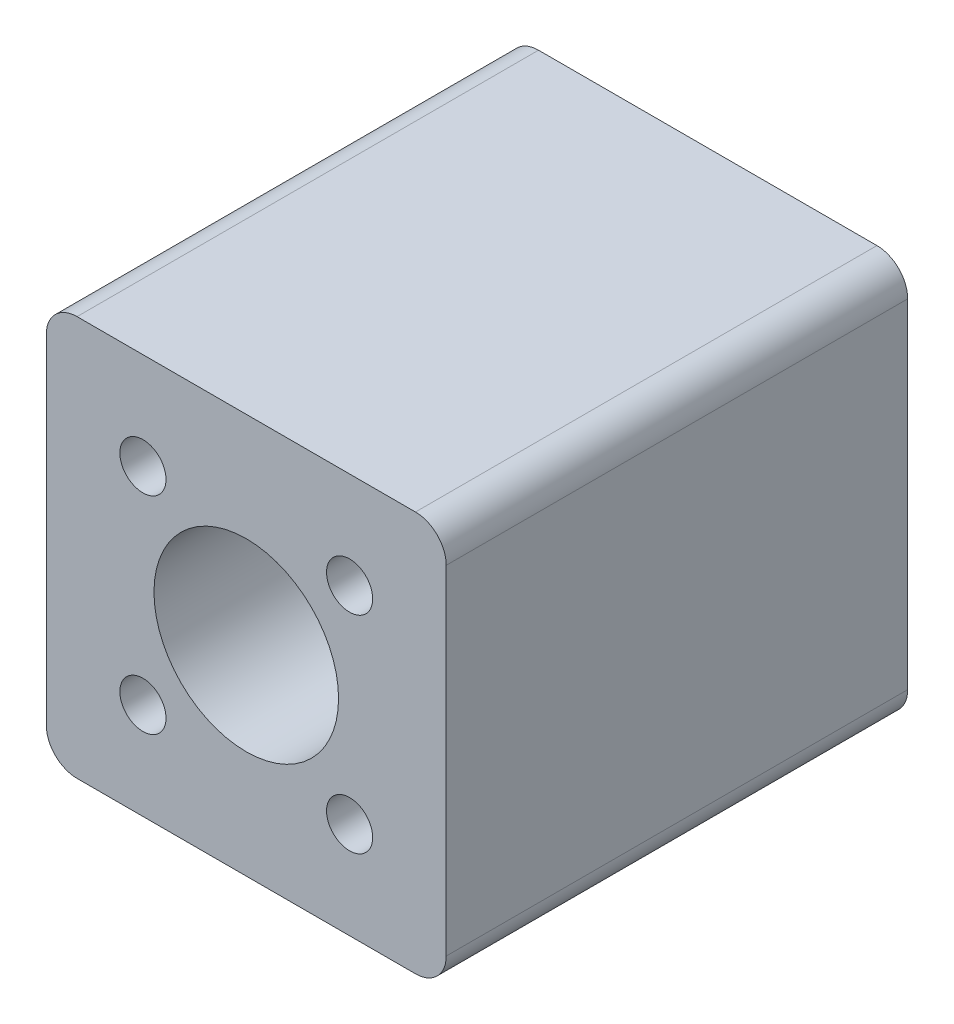
SolidWorks part; units mm, degrees
ref_plane "前视基准面" through (0, 0, 0) normal (0, 0, 1) x (1, 0, 0)
ref_plane "上视基准面" through (0, 0, 0) normal (0, 1, 0) x (1, 0, 0)
ref_plane "右视基准面" through (0, 0, 0) normal (1, 0, 0) x (0, 0, -1)
sketch "草图1" plane through (0, 0, 0) normal (0, 0, 1) x (1, 0, 0)
  line L0 (0, 13) -> (11, 13)
  line L1 (13, 11) -> (13, -11)
  line L2 (11, -13) -> (-11, -13)
  line L3 (-13, -11) -> (-13, 11)
  line L4 (-11, 13) -> (0, 13)
  circle A7 centre (-6.7175, 6.7175) radius 1.5
  circle A8 centre (6.7175, 6.7175) radius 1.5
  circle A9 centre (-6.7175, -6.7175) radius 1.5
  circle A10 centre (6.7175, -6.7175) radius 1.5
  circle A11 centre (0, 0) radius 6
  arc A12 (-13, 11) -> (-11, 13) centre (-11, 11) cw
  arc A13 (13, 11) -> (11, 13) centre (11, 11) ccw
  arc A14 (11, -13) -> (13, -11) centre (11, -11) ccw
  arc A15 (-13, -11) -> (-11, -13) centre (-11, -11) ccw
  dimension "D1" = 2
  dimension "D2" = 2
  dimension "D3" = 2
  dimension "D4" = 2
extrude "凸台-拉伸1" add sketch "草图1" along normal blind 30
